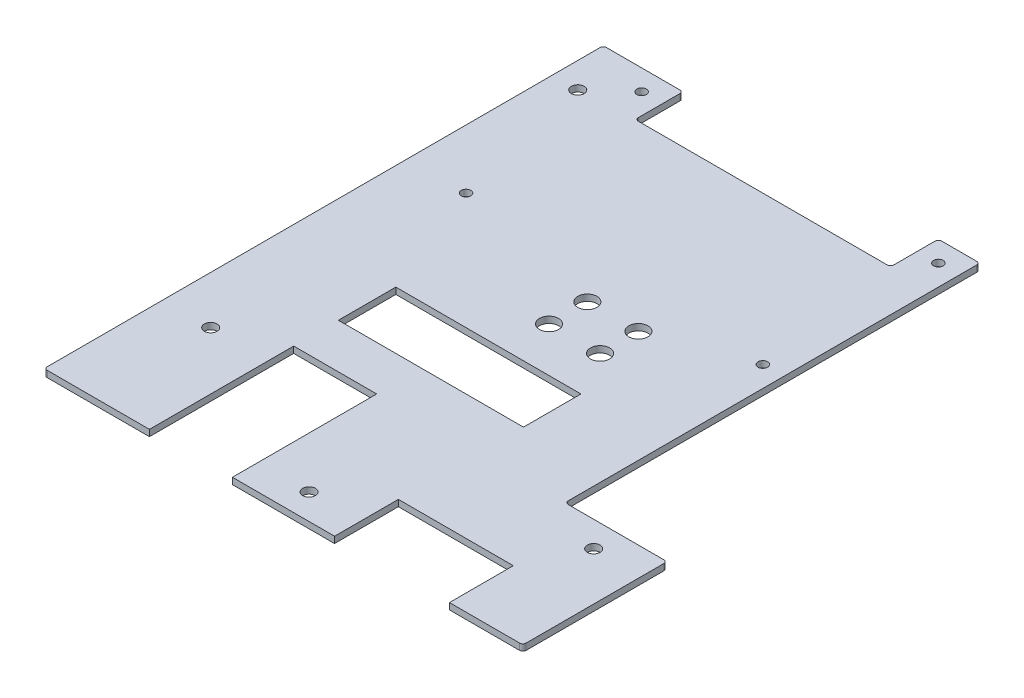
SolidWorks part; units mm, degrees
ref_plane "Alzado" through (0, 0, 0) normal (0, 0, 1) x (1, 0, 0)
ref_plane "Planta" through (0, 0, 0) normal (0, 1, 0) x (1, 0, 0)
ref_plane "Vista lateral" through (0, 0, 0) normal (1, 0, 0) x (0, 0, -1)
sketch "Croquis1" plane through (0, 0, 0) normal (0, 1, 0) x (1, 0, 0)
  line L1 (75.4, -88) -> (-75.4, -88) construction
  line L2 (75.4, -88) -> (75.4, 88) construction
  line L3 (75.4, 88) -> (-75.4, 88) construction
  line L4 (-75.4, -88) -> (-75.4, 88) construction
  line L5 (75.4, -88) -> (-75.4, 88) construction
  line L6 (75.4, 88) -> (-75.4, -88) construction
  line L7 (75, -87.6) -> (-75, -87.6)
  line L8 (75, -87.6) -> (75, 87.6)
  line L9 (75, 87.6) -> (-75, 87.6)
  line L10 (-75, -87.6) -> (-75, 87.6)
  line L11 (75, -87.6) -> (-75, 87.6) construction
  line L12 (75, 87.6) -> (-75, -87.6) construction
  line L13 (-59, 83.6) -> (39, 83.6) construction
  line L14 (-59, 83.6) -> (-59, 23.6) construction
  line L15 (-59, 23.6) -> (39, 23.6) construction
  line L16 (39, 83.6) -> (39, 23.6) construction
  line L17 (-59, 83.6) -> (39, 23.6) construction
  line L18 (-59, 23.6) -> (39, 83.6) construction
  line L19 (36.5, 26.1) -> (-56.5, 26.1) construction
  line L20 (36.5, 26.1) -> (36.5, 81.1) construction
  line L21 (36.5, 81.1) -> (-56.5, 81.1) construction
  line L22 (-56.5, 26.1) -> (-56.5, 81.1) construction
  line L23 (36.5, 26.1) -> (-56.5, 81.1) construction
  line L24 (36.5, 81.1) -> (-56.5, 26.1) construction
  circle A0 centre (-56.5, 81.1) radius 1.5
  circle A1 centre (36.5, 81.1) radius 1.5
  circle A2 centre (-56.5, 26.1) radius 1.5
  circle A3 centre (36.5, 26.1) radius 1.5
  point P0 (0, 0)
  point P6 (0, 0)
  point P11 (-10, 53.6)
  point P16 (-10, 53.6)
  point P17 (-10, 53.6)
  dimension "D9" = 3
  dimension "D1" = 150.8
  dimension "D2" = 176
  dimension "D3" = 0.4
  dimension "D4" = 0.4
  dimension "D5" = 98
  dimension "D6" = 60
  dimension "D7" = 93
  dimension "D8" = 55
  dimension "D10" = 16
  dimension "D11" = 4
extrude "Extruir1" add sketch "Croquis1" along normal blind 2
sketch "Croquis2" plane through (0, 2, 0) normal (0, 1, 0) x (1, 0, 0)
  line L0 (75, 87.6) -> (-75, 87.6) construction
  line L1 (-50, 87.6) -> (30, 87.6)
  line L2 (-50, 87.6) -> (-50, 72.6)
  line L3 (-50, 72.6) -> (30, 72.6)
  line L4 (30, 87.6) -> (30, 72.6)
  line L6 (-55, 81.1) -> (-55, 87.6) construction
  line L7 (36.5, 81.1) -> (-56.5, 81.1) construction
  line L8 (35, 81.1) -> (35, 87.6) construction
  circle A0 centre (-56.5, 81.1) radius 1.5 construction
  circle A1 centre (36.5, 81.1) radius 1.5 construction
  dimension "D1" = 15
  dimension "D2" = 5
  dimension "D3" = 5
extrude "Extruir2" cut sketch "Croquis2" against normal blind 10
sketch "Croquis3" plane through (0, 2, 0) normal (0, 1, 0) x (1, 0, 0)
  line L0 (75, 87.6) -> (30, 87.6) construction
  line L1 (43, 87.6) -> (75, 87.6)
  line L2 (43, 87.6) -> (43, -42.4)
  line L3 (43, -42.4) -> (75, -42.4)
  line L4 (75, 87.6) -> (75, -42.4)
  line L5 (75, -87.6) -> (75, 87.6) construction
  line L6 (38, 81.1) -> (38, 87.6) construction
  line L7 (75, 87.6) -> (-75, 87.6) construction
  line L8 (36.5, 81.1) -> (38, 81.1) construction
  line L9 (-59, 23.6) -> (39, 23.6) construction
  circle A0 centre (36.5, 81.1) radius 1.5 construction
  dimension "D1" = 5
  dimension "D2" = 130
extrude "Extruir3" cut sketch "Croquis3" against normal blind 10
sketch "Croquis4" plane through (0, 2, 0) normal (0, 1, 0) x (1, 0, 0)
  line L0 (75, -50.4) -> (-75, -50.4) construction
  line L1 (75, -87.6) -> (75, -42.4) construction
  line L2 (-75, 87.6) -> (-75, -87.6) construction
  line L4 (43, -42.4) -> (75, -42.4) construction
  line L5 (0, -50.4) -> (0, -87.6) construction
  line L6 (75, -87.6) -> (-75, -87.6) construction
  line L7 (-67, 87.6) -> (-67, -87.6) construction
  line L8 (75, 87.6) -> (-75, 87.6) construction
  line L9 (-75, -87.6) -> (-75, 87.6) construction
  circle A0 centre (-60, -50.4) radius 2
  circle A1 centre (60, -50.4) radius 2
  circle A2 centre (-67, 71.6) radius 2
  circle A3 centre (0, -79.6) radius 2
  dimension "D2" = 4
  dimension "D3" = 60
  dimension "D5" = 16
  dimension "D6" = 8
  dimension "D1" = 8
  dimension "D4" = 8
extrude "Extruir4" cut sketch "Croquis4" against normal blind 10
sketch "Croquis5" plane through (0, 2, 0) normal (0, 1, 0) x (1, 0, 0)
  line L0 (0, -87.6) -> (0, 0) construction
  line L1 (75, -87.6) -> (-75, -87.6) construction
  line L2 (-59, 23.6) -> (39, 23.6) construction
  line L3 (0, 3.6) -> (43, 3.6) construction
  line L4 (43, 87.6) -> (43, -42.4) construction
  circle A0 centre (0, 15.6) radius 3
  circle A1 centre (0, 3.6) radius 3
  dimension "D1" = 6
  dimension "D2" = 8
  dimension "D3" = 6
  dimension "D4" = 12
extrude "Extruir5" cut sketch "Croquis5" against normal blind 10
pattern_linear "MatrizL1" count 2 spacing 8 along (-1, 0, 0) count 2 spacing 8 along (1, 0, 0) of "Extruir5"
sketch "Croquis6" plane through (0, 2, 0) normal (0, 1, 0) x (1, 0, 0)
  circle A0 centre (0, 15.6) radius 3 construction
  circle A1 centre (0, 15.6) radius 3
  circle A2 centre (0, 3.6) radius 3 construction
  circle A3 centre (0, 3.6) radius 3
extrude "Extruir6" add sketch "Croquis6" against normal up to surface (2 mm away) up to face at (-8, 0, -0.6)
sketch "Croquis7" plane through (0, 2, 0) normal (0, 1, 0) x (1, 0, 0)
  line L0 (-42, -87.6) -> (-16, -87.6)
  line L1 (-42, -87.6) -> (-42, -42.4)
  line L2 (-42, -42.4) -> (-16, -42.4)
  line L3 (-16, -87.6) -> (-16, -42.4)
  line L4 (0, 117.1634) -> (0, 65.5634) construction
  line L5 (16, -87.6) -> (52, -87.6)
  line L6 (16, -87.6) -> (16, -67.6)
  line L7 (16, -67.6) -> (52, -67.6)
  line L8 (52, -87.6) -> (52, -67.6)
  line L9 (-42, -10.4) -> (16, -10.4)
  line L10 (-42, -10.4) -> (-42, -28.4)
  line L11 (-42, -28.4) -> (16, -28.4)
  line L12 (16, -10.4) -> (16, -28.4)
  line L13 (-75, -87.6) -> (75, -87.6) construction
  line L14 (0, 0) -> (0, 72.6) construction
  line L15 (-50, 72.6) -> (30, 72.6) construction
  line L16 (43, -42.4) -> (75, -42.4) construction
  circle A0 centre (-8, 3.6) radius 3 construction
  dimension "D1" = 26
  dimension "D2" = 16
  dimension "D3" = 36
  dimension "D4" = 20
  dimension "D5" = 14
  dimension "D6" = 16
  dimension "D7" = 14
extrude "Extruir7" cut sketch "Croquis7" against normal blind 10
fillet "Redondeo1" radius 1 10 edges at (30, 1, -72.6) (-75, 1, -87.6) (-50, 1, -87.6) (-50, 1, -72.6) (30, 1, -87.6) (43, 1, -87.6) (43, 1, 42.4) (75, 1, 42.4) (75, 1, 87.6) (-75, 1, 87.6)
